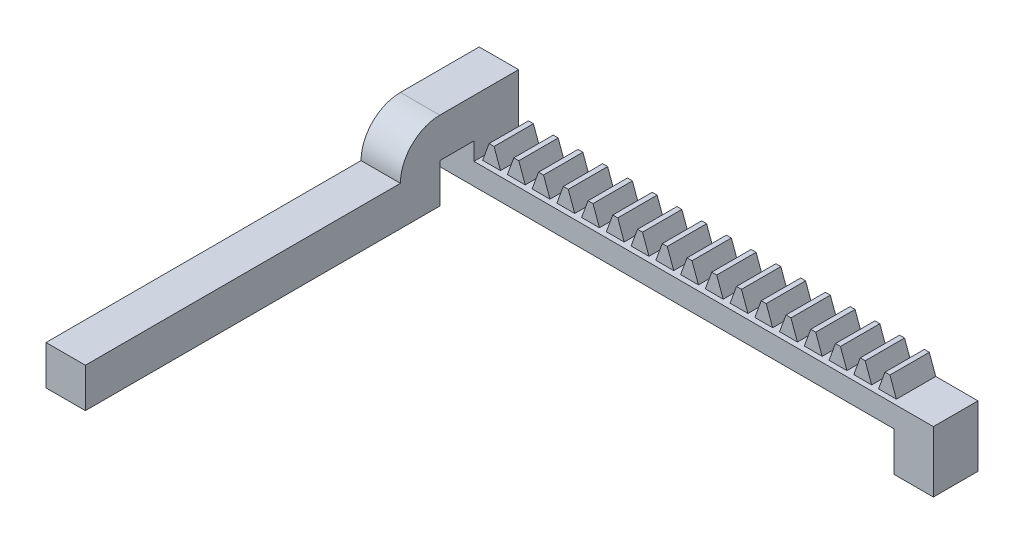
SolidWorks part; units mm, degrees
extrude "Blank" add sketch "BlankSke" against normal blind 20
sketch "BlankSke" plane through (0, 0, 0) normal (0, 0, 1) x (1, 0, 0)
  line L1 (0, 0) -> (80, 0)
  line L2 (0, 0) -> (0, 7.5)
  line L3 (0, 7.5) -> (80, 7.5)
  line L4 (80, 0) -> (80, 7.5)
  dimension "Length" = 80
  dimension "Blank_height" = 7.5
ref_plane "Plane1" through (0, 0, 0) normal (0, 0, 1) x (1, 0, 0)
ref_plane "Plane2" through (0, 0, 0) normal (0, 1, 0) x (1, 0, 0)
ref_plane "Plane3" through (0, 0, 0) normal (1, 0, 0) x (0, 0, -1)
sketch "HoldingSke" plane through (0, 0, 0) normal (0, 1, 0) x (1, 0, 0)
  line L0 (0, 0) -> (0.0928, 0.6602)
  line L1 (-15, 0) -> (100, 0) construction
  line L2 (0, 0) -> (-2.1039, 2.3779)
  line L3 (0, 0) -> (-11.863, 4.5341)
  line L4 (0, 0) -> (8.2133, 2.6687)
  line L5 (0, 0) -> (-23.7986, -8.8762)
  line L6 (0, 0) -> (-10.5278, -7.1032)
  line L9 (-71.009, 38.7566) -> (4.1664, 66.1182)
  line L10 (-76.2, 3.8779) -> (-70.2, 3.8779)
  line L11 (0, 0) -> (-20, 0)
  line L12 (-76.2, 101.6) -> (-76.147, 101.6)
  line L13 (24.9733, 27.94) -> (52.9518, 28.4284)
  line L14 (24.9733, 27.94) -> (24.9743, 27.94)
  line L15 (24.9733, 27.94) -> (100.4006, 29.5858)
  circle A0 centre (0, 0) radius 19.05
  circle A1 centre (0, 0) radius 3
  circle A2 centre (0, 0) radius 12.7
  dimension "MPH" = 6
  dimension "Diameter" = 38.1
  dimension "Num_teeth" = 18
  dimension "Pitch" = 0.6667
  dimension "Show_teeth" = 998
  dimension "Thickness" = 12.7
  dimension "Ap" = 20
  dimension "Pitch_height" = 6
  dimension "Width" = 20
  dimension "Backlash" = 0.053
  dimension "Addendum_fac" = 1
  dimension "Dedendum_fac" = 1.25
  dimension "Clearance_fac" = 0.25
  dimension "Dedendum_add" = 0.001
  dimension "Length" = 80
  dimension "Module" = 1.5
sketch "TooCutSkeIll" plane through (0, 0, 0) normal (0, 0, 1) x (1, 0, 0)
  line L0 (-1.8687, 7.4605) -> (-0.7447, 4.3724)
  line L1 (-0.3914, 4.125) -> (0.3914, 4.125)
  line L2 (0.7447, 4.3724) -> (1.8687, 7.4605)
  line L3 (80, 7.5) -> (0, 7.5) construction
  line L4 (0, 0) -> (0, 64.897) construction
  line L5 (-13.208, 6) -> (12.954, 6) construction
  line L6 (0, 0) -> (80, 0) construction
  line L7 (1.3371, 6) -> (1.3371, 48.7463) construction
  line L8 (-1.3371, 6) -> (-1.3371, 48.7463) construction
  line L9 (1.9251, 7.5) -> (1.9251, 7.5254)
  line L10 (-1.9251, 7.5) -> (-1.9251, 7.5254)
  line L11 (-1.9251, 7.5254) -> (1.9251, 7.5254)
  arc A0 (0.3914, 4.125) -> (0.7447, 4.3724) centre (0.3914, 4.501) ccw
  arc A1 (-0.7447, 4.3724) -> (-0.3914, 4.125) centre (-0.3914, 4.501) ccw
  arc A2 (1.9251, 7.5) -> (1.8687, 7.4605) centre (1.9251, 7.44) ccw
  arc A3 (-1.8687, 7.4605) -> (-1.9251, 7.5) centre (-1.9251, 7.44) ccw
  dimension "Pitch_height" = 6
  dimension "Addendum_plus" = 1.5254
  dimension "Pressure_angle" = 20
  dimension "Gap_width" = 2.6742
  dimension "Dedendum" = 1.875
extrude "ToothCutIll" [suppressed] cut sketch "TooCutSkeIll" against normal through all
sketch "TooCutSkeSim" plane through (0, 0, 0) normal (0, 0, 1) x (1, 0, 0)
  line L0 (0.6547, 4.125) -> (-0.6547, 4.125)
  line L1 (1.8923, 7.5254) -> (0.6547, 4.125)
  line L2 (0, 17.4625) -> (0, 53.467) construction
  line L3 (1.8923, 7.5254) -> (-1.8923, 7.5254)
  line L6 (-1.8923, 7.5254) -> (-0.6547, 4.125)
  line L9 (-1.3371, 6) -> (1.3371, 6) construction
  line L10 (0, 0) -> (80, 0) construction
  line L11 (1.3371, 6) -> (1.3371, 53.467) construction
  line L12 (-1.3371, 6) -> (-1.3371, 53.467) construction
  dimension "Pitch_height" = 6
  dimension "Addendum_plus" = 1.5254
  dimension "Pressure_angle" = 20
  dimension "Gap_width" = 2.6742
  dimension "Dedendum" = 1.875
extrude "ToothCutSim" cut sketch "TooCutSkeSim" against normal through all
pattern_linear "TeethCuts" count 18 spacing 4.7124 along (1, 0, 0) of "ToothCutIll", "ToothCutSim"
sketch "Sketch1" plane through (80, 0, 0) normal (1, 0, 0) x (0, 0, -1)
  line L1 (0, 4.125) -> (20, 4.125)
  line L2 (0, 4.125) -> (0, -7.5)
  line L3 (0, -7.5) -> (20, -7.5)
  line L4 (20, 4.125) -> (20, -7.5)
  line L7 (20, 0) -> (20, 4.125) construction
  dimension "D1" = 11.625
  dimension "D2" = 0
extrude "Boss-Extrude2" add sketch "Sketch1" along normal blind 7.5
sketch "Sketch3" plane through (0, 0, 0) normal (-1, 0, 0) x (0, 0, 1)
  line L1 (-20, 0) -> (0, 0)
  line L2 (-20, 0) -> (-20, 15)
  line L3 (-20, 15) -> (0, 15)
  line L4 (0, 0) -> (0, 15)
  line L5 (0, 4.125) -> (0, 0) construction
  dimension "D1" = 15
  dimension "D2" = 0
extrude "Boss-Extrude3" add sketch "Sketch3" along normal blind 7.5
sketch "Sketch4" plane through (0, 0, 0) normal (0, 0, 1) x (1, 0, 0)
  line L1 (-7.5, 0) -> (0, 0)
  line L2 (-7.5, 0) -> (-7.5, 15)
  line L3 (-7.5, 15) -> (0, 15)
  line L4 (0, 0) -> (0, 15)
extrude "Boss-Extrude4" add sketch "Sketch4" along normal blind 15
sketch "Sketch8" plane through (0, 0, 0) normal (1, 0, 0) x (0, 0, -1)
  line L1 (0, 0) -> (-7.5, 0)
  line L2 (0, 0) -> (0, 7.5)
  line L3 (0, 7.5) -> (-7.5, 7.5)
  line L4 (-7.5, 0) -> (-7.5, 7.5)
  dimension "D1" = 7.5
  dimension "D2" = 7.5
extrude "Cut-Extrude1" cut sketch "Sketch8" against normal blind 15
sketch "Sketch9" plane through (-7.5, 0, 0) normal (-1, 0, 0) x (0, 0, 1)
  line L0 (7.5, 15) -> (15, 7.5)
  line L1 (15, 15) -> (-20, 15) construction
  line L2 (15, 15) -> (15, 0) construction
  line L3 (7.5, 15) -> (15, 15)
  line L4 (15, 15) -> (15, 7.5)
  dimension "D1" = 7.5
  dimension "D2" = 7.5
extrude "Cut-Extrude2" cut sketch "Sketch9" against normal blind 15
sketch "Sketch10" plane through (0, 0, 0) normal (0, -1, 0) x (1, 0, 0)
  line L1 (-7.5, 7.5) -> (0, 7.5)
  line L2 (-7.5, 7.5) -> (-7.5, 15)
  line L3 (-7.5, 15) -> (0, 15)
  line L4 (0, 7.5) -> (0, 15)
extrude "Boss-Extrude5" add sketch "Sketch10" along normal blind 7.5
sketch "Sketch11" plane through (0, 0, 15) normal (0, 0, 1) x (1, 0, 0)
  line L1 (-7.5, 7.5) -> (0, 7.5)
  line L2 (-7.5, 7.5) -> (-7.5, -7.5)
  line L3 (-7.5, -7.5) -> (0, -7.5)
  line L4 (0, 7.5) -> (0, -7.5)
  line L5 (-7.5, -7.5) -> (0, -7.5)
  line L6 (-7.5, -7.5) -> (-7.5, 7.5)
  line L7 (-7.5, 7.5) -> (0, 7.5)
  line L8 (0, -7.5) -> (0, 7.5)
  line M1 (0, -7.5) -> (0, 7.5)
  line M2 (0, 7.5) -> (-7.5, 7.5)
  line M3 (-7.5, 7.5) -> (-7.5, -7.5)
  line M4 (-7.5, -7.5) -> (0, -7.5)
extrude "Boss-Extrude7" add sketch "Sketch11" along normal blind 60 contours M4 M1 M2 M3
sketch "Sketch12" plane through (0, 4.125, 0) normal (0, 1, 0) x (1, 0, 0)
  line L0 (87.5, 20) -> (87.5, 0) construction
  line L1 (-7.5, 20) -> (87.5, 20)
  line L2 (-7.5, 20) -> (-7.5, 10)
  line L3 (-7.5, 10) -> (87.5, 10)
  line L4 (87.5, 20) -> (87.5, 10)
extrude "Cut-Extrude4" cut sketch "Sketch12" along normal through all both and the other way through all
sketch "Sketch14" plane through (0, 15, 0) normal (0, 1, 0) x (1, 0, 0)
  line L0 (87.5, 10) -> (87.5, 0) construction
  line L1 (-7.5, 10) -> (87.5, 10)
  line L2 (-7.5, 10) -> (-7.5, 7.5)
  line L3 (-7.5, 7.5) -> (87.5, 7.5)
  line L4 (87.5, 10) -> (87.5, 7.5)
  dimension "D1" = 2.5
extrude "Cut-Extrude5" cut sketch "Sketch14" against normal blind 100
sketch "Sketch15" plane through (-7.5, 0, 0) normal (-1, 0, 0) x (0, 0, 1)
  line L0 (75, 7.5) -> (75, -7.5) construction
  line L1 (7.5, -7.5) -> (75, -7.5)
  line L2 (7.5, -7.5) -> (7.5, 0)
  line L3 (7.5, 0) -> (75, 0)
  line L4 (75, -7.5) -> (75, 0)
extrude "Cut-Extrude6" cut sketch "Sketch15" against normal through all
sketch "Sketch16" plane through (-7.5, 0, 0) normal (-1, 0, 0) x (0, 0, 1)
  line L0 (7.5, 7.5) -> (7.5, 15)
  line L1 (15, 7.5) -> (7.5, 7.5)
  arc A0 (7.5, 15) -> (15, 7.5) centre (7.5, 7.5) cw
extrude "Boss-Extrude8" add sketch "Sketch16" against normal up to vertex (7.5 mm away) up to point (0, 15, 7.5)
sketch "Sketch19" plane through (0, 0, 0) normal (0, 0, 1) x (1, 0, 0)
  line L0 (-7.5, 0) -> (-7.5, 7.5)
  line L1 (-7.5, 7.5) -> (0, 7.5)
  line L2 (0, 7.5) -> (0, 4.125)
  line L3 (0, 4.125) -> (87.5, 4.125)
  line L4 (87.5, 4.125) -> (87.5, -7.5)
  line L5 (87.5, -7.5) -> (80, -7.5)
  line L6 (80, -7.5) -> (80, 0)
  line L7 (80, 0) -> (-7.5, 0)
extrude "Boss-Extrude9" add sketch "Sketch19" along normal blind 1
equation "' \"Module@HoldingSke\" = 6.35"
equation "' \"Num_teeth@HoldingSke\" = 12"
equation "' \"Ap@HoldingSke\" =  20"
equation "' \"Ap@HoldingSke\" = 20"
equation "' \"Width@HoldingSke\" = 0.25 * 25.4"
equation "' \"Show_teeth@HoldingSke\" = 500"
equation "' \"Backlash@HoldingSke\" = 0.009 * 25.4"
equation "' \"Addendum_fac@HoldingSke\" = 1.0"
equation "' \"Dedendum_fac@HoldingSke\" = 1.25"
equation "' \"Dedendum_add@HoldingSke\" = 0.00005 * 25.4"
equation "' \"Clearance_fac@HoldingSke\" = 0.25"
equation "' \"Pitch_height@HoldingSke\" = 1 * 25.4"
equation "' \"Length@HoldingSke\" = 4.71 * 25.4"
equation "\"Pitch@HoldingSke\" = 1 / \"Module@HoldingSke\""
equation "\"MPH@HoldingSke\" = \"Dedendum_fac@HoldingSke\" / \"Pitch@HoldingSke\" + 2 * \"Dedendum_add@HoldingSke\" + 0.002 * 25.4"
equation "\"MPH@HoldingSke\" = ((sgn( \"MPH@HoldingSke\" - \"Pitch_height@HoldingSke\")+1)*( \"MPH@HoldingSke\" - \"Pitch_height@HoldingSke\"))/2 + \"Pitch_height@HoldingSke\""
equation "\"Blank_height@BlankSke\" = \"Pitch_height@HoldingSke\" + \"Addendum_fac@HoldingSke\"  / \"Pitch@HoldingSke\" "
equation "\"Length@BlankSke\" =  \"Length@HoldingSke\""
equation "\"Face_width@Blank\" = \"Width@HoldingSke\""
equation "\"Pressure_angle@TooCutSkeIll\" = \"Ap@HoldingSke\""
equation "\"Addendum_plus@TooCutSkeIll\" =  \"Addendum_fac@HoldingSke\"  / \"Pitch@HoldingSke\" + 0.001 *25.4"
equation "\"Dedendum@TooCutSkeIll\" = \"Dedendum_fac@HoldingSke\"  / \"Pitch@HoldingSke\""
equation "\"Pitch_height@TooCutSkeIll\" =  \"MPH@HoldingSke\""
equation "\"Gap_width@TooCutSkeIll\" = 3.14159265 / 2 / \"Pitch@HoldingSke\" + 6 * \"Backlash@HoldingSke\""
equation "\"Pressure_angle@TooCutSkeSim\" = \"Ap@HoldingSke\""
equation "\"Addendum_plus@TooCutSkeSim\" =  \"Addendum_fac@HoldingSke\"  / \"Pitch@HoldingSke\" + 0.001 * 25.4"
equation "\"Dedendum@TooCutSkeSim\" = \"Dedendum_fac@HoldingSke\"  / \"Pitch@HoldingSke\""
equation "\"Pitch_height@TooCutSkeSim\" =  \"MPH@HoldingSke\""
equation "\"Gap_width@TooCutSkeSim\" = 3.14159265 / 2 / \"Pitch@HoldingSke\" + 6 * \"Backlash@HoldingSke\""
equation "\"Root_fillet@TooCutSkeIll\" = \"Clearance_fac@HoldingSke\" / \"Pitch@HoldingSke\" + \"Dedendum_add@HoldingSke\""
equation "\"Break_rad@TooCutSkeIll\" = 0.02 / \"Pitch@HoldingSke\" * 2"
equation "\"Linear_pitch@TeethCuts\" = 3.14159265 / \"Pitch@HoldingSke\""
equation "\"Num_teeth@HoldingSke\" = int( ( \"Length@HoldingSke\" + 0 ) / (3.14159265 / \"Pitch@HoldingSke\")) + 0.9999  + 1"
equation " \"Num_teeth@TeethCuts\" = int( \"Show_teeth@HoldingSke\" ) + 1"
equation " \"Num_teeth@TeethCuts\" = ((sgn( \"Num_teeth@TeethCuts\" - \"Num_teeth@HoldingSke\" )-1)*( \"Num_teeth@TeethCuts\" - \"Num_teeth@HoldingSke\" ))/-2+ \"Num_teeth@HoldingSke\""
equation " \"Num_teeth@TeethCuts\" = ((sgn( \"Num_teeth@TeethCuts\" - 2.0)+1)*( \"Num_teeth@TeethCuts\" - 2.0))/2 +2.0"
